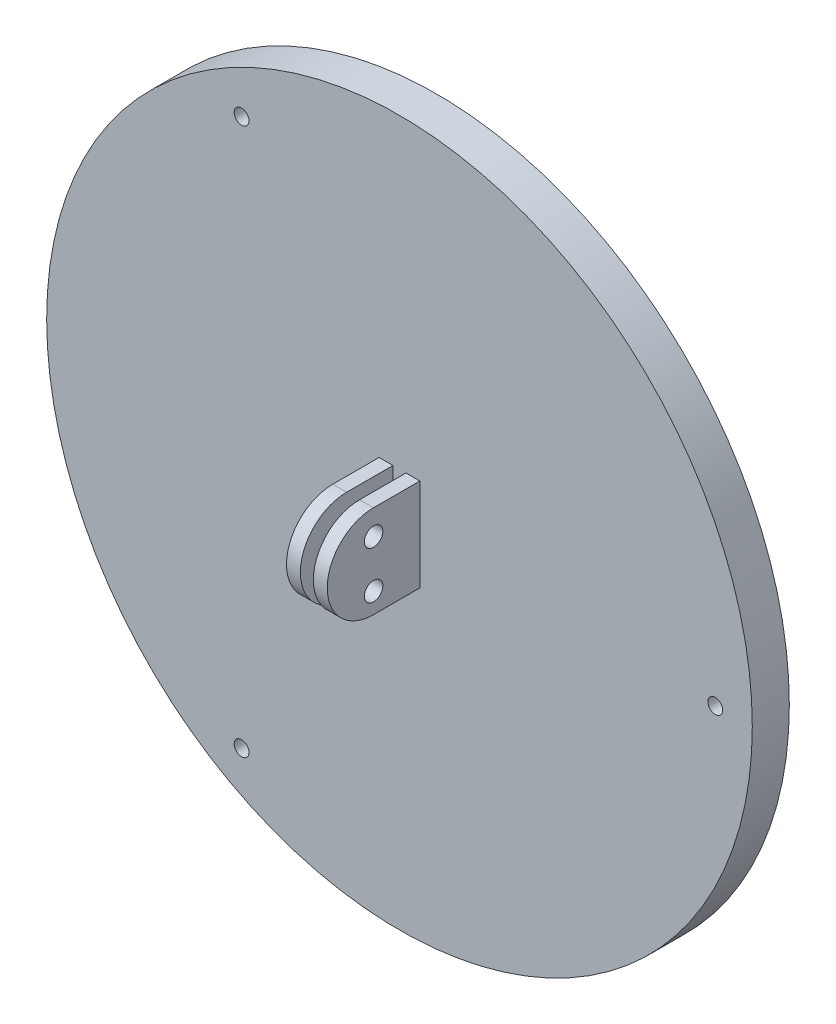
SolidWorks part; units mm, degrees
ref_plane "Front Plane" through (0, 0, 0) normal (0, 0, 1) x (1, 0, 0)
ref_plane "Top Plane" through (0, 0, 0) normal (0, 1, 0) x (1, 0, 0)
ref_plane "Right Plane" through (0, 0, 0) normal (1, 0, 0) x (0, 0, -1)
sketch "Sketch2" plane through (0, 0, 0) normal (0, 0, 1) x (1, 0, 0)
  circle A0 centre (0, 0) radius 38.1
  point P11 (0, 0)
  dimension "D1" = 76.2
extrude "Boss-Extrude1" add sketch "Sketch2" along normal blind 4 contours A0
sketch "Sketch3" plane through (0, 0, 4) normal (0, 0, 1) x (1, 0, 0)
  circle A0 centre (34.1, -0.0857) radius 0.8
  circle A1 centre (-17.05, -29.6172) radius 0.8
  circle A2 centre (-17.05, 29.4457) radius 0.8
  point P8 (0, -0.0857)
  dimension "D1" = 1.6
  dimension "D3" = 34.1
  dimension "D2" = 3
extrude "Cut-Extrude1" cut sketch "Sketch3" against normal blind 6
sketch "Sketch4" plane through (0, 0, 4) normal (0, 0, 1) x (1, 0, 0)
  circle A0 centre (0, 0) radius 0.6
  dimension "D1" = 1.2
extrude "Cut-Extrude2" cut sketch "Sketch4" against normal blind 6
sketch "Sketch5" plane through (0, 0, 4) normal (0, 0, 1) x (1, 0, 0)
  line L1 (0.7, 5) -> (2.2, 5)
  line L2 (0.7, 5) -> (0.7, -5)
  line L3 (0.7, -5) -> (2.2, -5)
  line L4 (2.2, 5) -> (2.2, -5)
  line L5 (-0.7, 5) -> (-2.2, 5)
  line L6 (-0.7, 5) -> (-0.7, -5)
  line L7 (-0.7, -5) -> (-2.2, -5)
  line L8 (-2.2, 5) -> (-2.2, -5)
  dimension "D1" = 10
  dimension "D2" = 1.5
  dimension "D3" = 2.2
  dimension "D4" = 5
  dimension "D5" = 2.2
  dimension "D6" = 5
extrude "Boss-Extrude2" add sketch "Sketch5" along normal blind 10
sketch "Sketch6" plane through (2.2, 0, 0) normal (1, 0, 0) x (0, 0, -1)
  line L0 (-14, -5) -> (-4, -5) construction
  line L1 (-14, 5) -> (-4, 5) construction
  line L2 (-9, 5) -> (-14, 5)
  line L3 (-14, 5) -> (-14, -5)
  line L5 (-14, -5) -> (-9, -5)
  line L6 (-14, 5) -> (-9, 5)
  arc A2 (-9, -5) -> (-9, 5) centre (-9, 0) cw
  point P1 (-9, -5)
  point P2 (-9.1485, 5)
  line M5 (-4, 5) -> (-14, 5)
  line M6 (-14, 5) -> (-14, -5)
  line M7 (-14, -5) -> (-4, -5)
extrude "Cut-Extrude3" cut sketch "Sketch6" against normal through all contours A2 M6 M5 | A2 L3 M7
sketch "Sketch7" plane through (2.2, 0, 0) normal (1, 0, 0) x (0, 0, -1)
  line L1 (-9, 5) -> (-4, 5) construction
  line L2 (-9, -5) -> (-4, -5) construction
  circle A2 centre (-9, 2.3) radius 1
  circle A3 centre (-9, -2.8) radius 1
  dimension "D1" = 2.7
  dimension "D2" = 2.2
  dimension "D4" = 2
extrude "Cut-Extrude4" cut sketch "Sketch7" against normal through all
